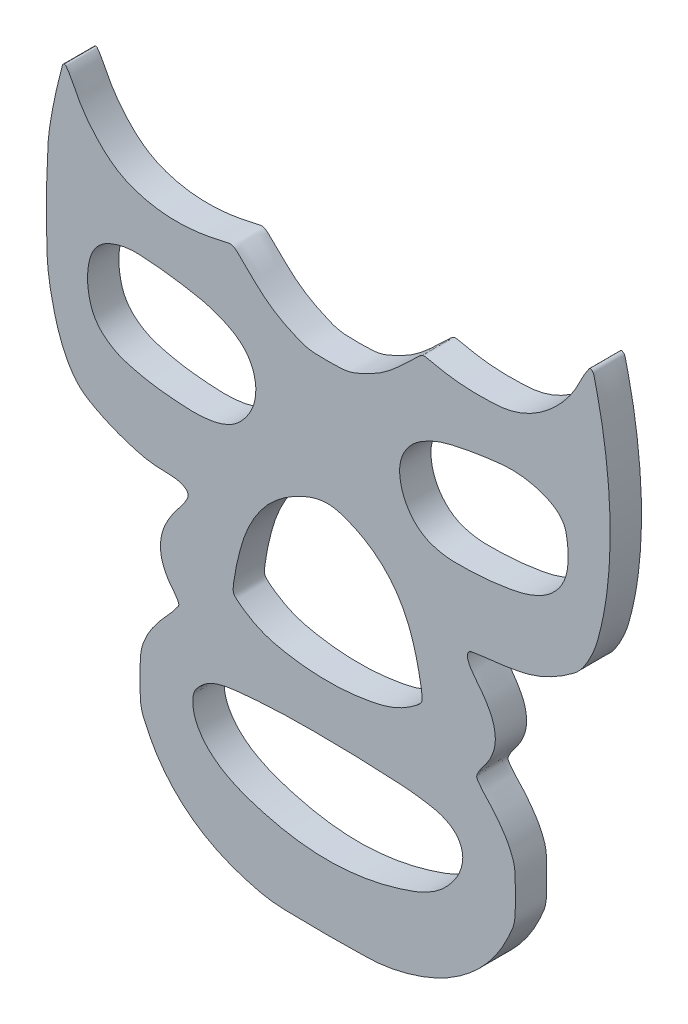
SolidWorks part; units mm, degrees
ref_plane "Alzado" through (0, 0, 0) normal (0, 0, 1) x (1, 0, 0)
ref_plane "Planta" through (0, 0, 0) normal (0, 1, 0) x (1, 0, 0)
ref_plane "Vista lateral" through (0, 0, 0) normal (1, 0, 0) x (0, 0, -1)
sketch "Model" plane through (0, 0, 0) normal (0, 0, 1) x (1, 0, 0)
  spline S0 degree 3 number of poles 1471 (222.8465, 148.1472) -> (222.8465, 148.1472)
  spline S1 degree 3 number of poles 210 (212.7754, 223.8844) -> (212.7754, 223.8844)
  spline S2 degree 3 number of poles 205 (370.9101, 223.6013) -> (370.9101, 223.6013)
  spline S3 degree 3 number of poles 205 (283.4695, 172.8631) -> (283.4695, 172.8631)
  spline S4 degree 3 number of poles 257 (334.3357, 80.9878) -> (334.3357, 80.9878)
extrude "Saliente-Extruir1" add sketch "Model" along normal blind 13.35
